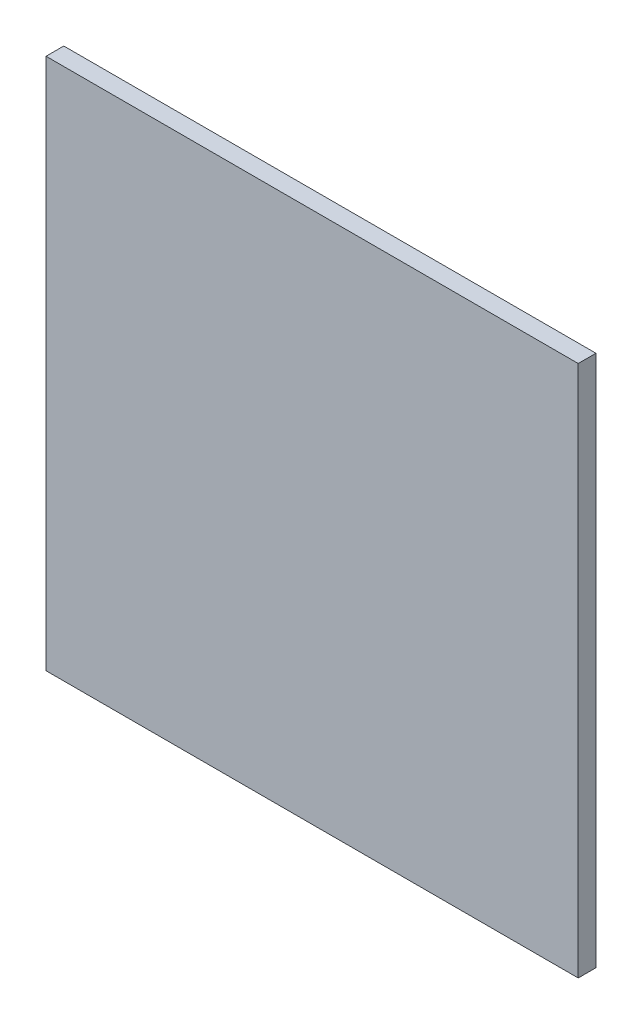
SolidWorks part; units mm, degrees
ref_plane "Plan de face" through (0, 0, 0) normal (0, 0, 1) x (1, 0, 0)
ref_plane "Plan de dessus" through (0, 0, 0) normal (0, 1, 0) x (1, 0, 0)
ref_plane "Plan de droite" through (0, 0, 0) normal (1, 0, 0) x (0, 0, -1)
sketch "Esquisse1" plane through (0, 0, 0) normal (0, 0, 1) x (1, 0, 0)
  line L1 (26.9163, 20.7004) -> (-33.0837, 20.7004)
  line L2 (26.9163, 20.7004) -> (26.9163, -39.2996)
  line L3 (26.9163, -39.2996) -> (-33.0837, -39.2996)
  line L4 (-33.0837, 20.7004) -> (-33.0837, -39.2996)
  dimension "D1" = 60
  dimension "D2" = 60
extrude "Boss.-Extru.1" add sketch "Esquisse1" along normal blind 2
